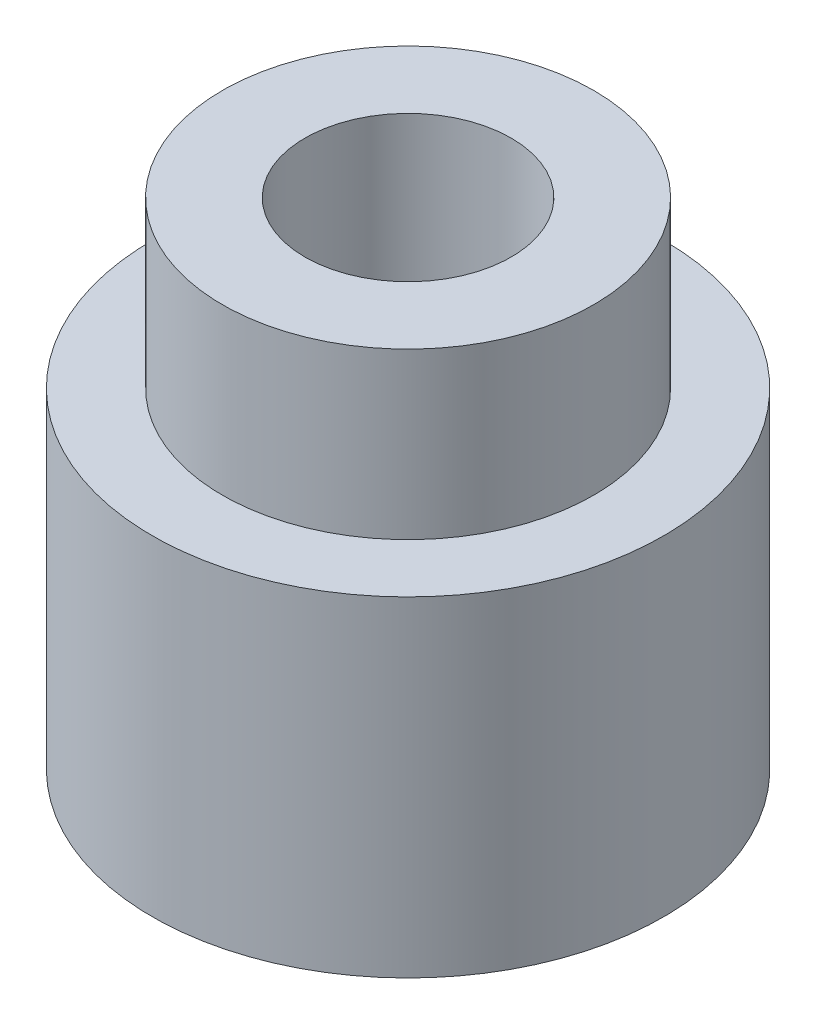
SolidWorks part; units mm, degrees
ref_plane "Front Plane" through (0, 0, 0) normal (0, 0, 1) x (1, 0, 0)
ref_plane "Top Plane" through (0, 0, 0) normal (0, 1, 0) x (1, 0, 0)
ref_plane "Right Plane" through (0, 0, 0) normal (1, 0, 0) x (0, 0, -1)
sketch "Sketch1" plane through (0, 0, 0) normal (1, 0, 0) x (0, 0, -1)
  line L0 (0, 0) -> (0, 27.9576) construction
  line L1 (-6.2, 0) -> (-6.2, 8)
  line L2 (-6.2, 8) -> (-4.5, 8)
  line L3 (-4.5, 8) -> (-4.5, 12)
  line L4 (-4.5, 12) -> (-2.5, 12)
  line L5 (-2.5, 12) -> (-2.5, 6)
  line L6 (-2.5, 6) -> (-4.2, 6)
  line L7 (-4.2, 6) -> (-4.2, 0)
  line L8 (-4.2, 0) -> (-6.2, 0)
  dimension "D1" = 2.5
  dimension "D2" = 4.2
  dimension "D3" = 2
  dimension "D4" = 2
  dimension "D5" = 12
  dimension "D6" = 6
  dimension "D7" = 4
revolve "Revolve1" add sketch "Sketch1" angle 360 about L0
